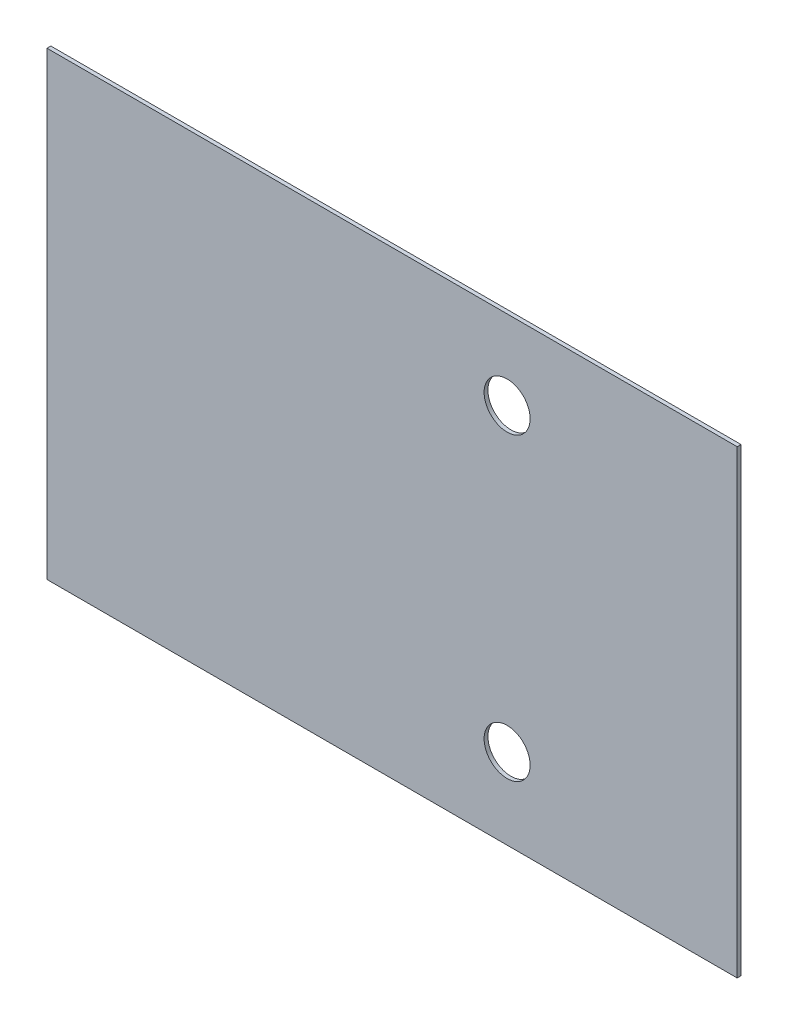
SolidWorks part; units mm, degrees
ref_plane "Front Plane" through (0, 0, 0) normal (0, 0, 1) x (1, 0, 0)
ref_plane "Top Plane" through (0, 0, 0) normal (0, 1, 0) x (1, 0, 0)
ref_plane "Right Plane" through (0, 0, 0) normal (1, 0, 0) x (0, 0, -1)
sketch "Sketch1" plane through (0, 0, 0) normal (0, 0, 1) x (1, 0, 0)
  line L1 (475.5459, 38.6463) -> (-424.4541, 38.6463)
  line L2 (475.5459, 38.6463) -> (475.5459, 638.6463)
  line L3 (475.5459, 638.6463) -> (-424.4541, 638.6463)
  line L4 (-424.4541, 38.6463) -> (-424.4541, 638.6463)
  dimension "D1" = 900
  dimension "D2" = 600
extrude "Boss-Extrude1" add sketch "Sketch1" along normal blind 5
sketch "Sketch2" plane through (0, 0, 0) normal (0, 0, -1) x (-1, 0, 0)
  line L0 (-475.5459, 38.6463) -> (-475.5459, 638.6463) construction
  circle A2 centre (-175.5459, 535.1286) radius 30
  circle A3 centre (-363.5131, 165.2274) radius 30
  dimension "D1" = 60
  dimension "D2" = 60
  dimension "D3" = 300
extrude "Cut-Extrude2" cut sketch "Sketch2" against normal blind 10 contours A2
sketch "Sketch3" plane through (0, 0, 0) normal (0, 0, -1) x (-1, 0, 0)
  line L0 (-475.5459, 38.6463) -> (-475.5459, 638.6463) construction
  circle A0 centre (-175.5459, 143.9381) radius 30
  dimension "D1" = 300
extrude "Cut-Extrude3" cut sketch "Sketch3" against normal blind 10
